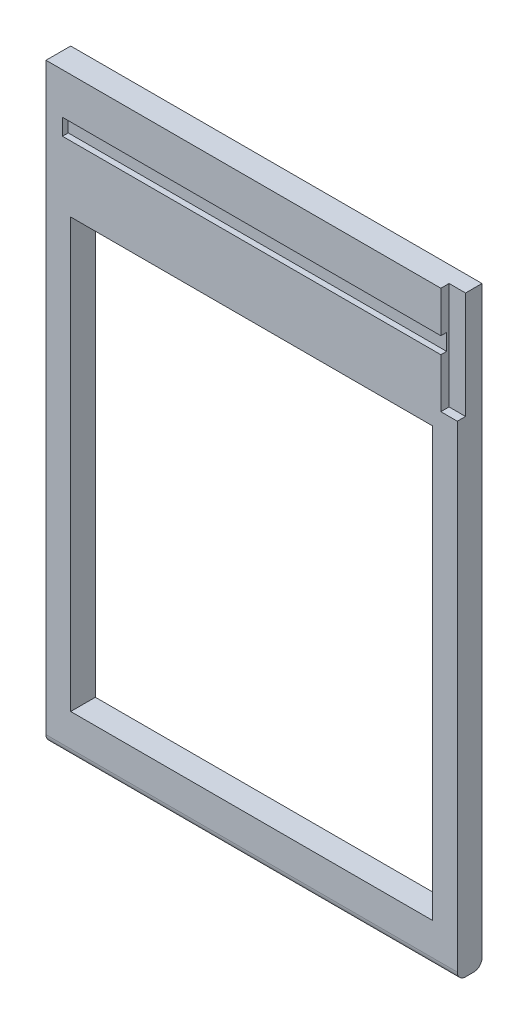
SolidWorks part; units mm, degrees
ref_plane "Alzado" through (0, 0, 0) normal (0, 0, 1) x (1, 0, 0)
ref_plane "Planta" through (0, 0, 0) normal (0, 1, 0) x (1, 0, 0)
ref_plane "Vista lateral" through (0, 0, 0) normal (1, 0, 0) x (0, 0, -1)
sketch "Croquis2" plane through (0, 0, 0) normal (0, 0, 1) x (1, 0, 0)
  line L1 (250, -360) -> (-250, -360)
  line L2 (250, -360) -> (250, 360)
  line L3 (250, 360) -> (-250, 360)
  line L4 (-250, -360) -> (-250, 360)
  line L5 (250, -360) -> (-250, 360) construction
  line L6 (250, 360) -> (-250, -360) construction
  point P0 (0, 0)
  dimension "D1" = 720
  dimension "D2" = 500
extrude "Saliente-Extruir1" add sketch "Croquis2" along normal blind 30
sketch "Croquis3" plane through (0, 0, 0) normal (0, 0, -1) x (-1, 0, 0)
  line L0 (-250, 360) -> (250, 360) construction
  line L1 (220, -310.6162) -> (-220, -310.6162)
  line L2 (220, -310.6162) -> (220, 210)
  line L3 (220, 210) -> (-220, 210)
  line L4 (-220, -310.6162) -> (-220, 210)
  line L5 (220, -310.6162) -> (-220, 210) construction
  line L6 (220, 210) -> (-220, -310.6162) construction
  line L7 (-250, -360) -> (-250, 360) construction
  line L9 (250, 360) -> (250, -360) construction
  point P0 (0, -50.3081)
  dimension "D1" = 150
  dimension "D2" = 440
  dimension "D3" = 30
  dimension "D4" = 30
extrude "Cortar-Extruir1" cut sketch "Croquis3" against normal through all
fillet "Redondeo1" radius 10 1 edges at (0, -360, 0)
fillet "Redondeo2" radius 10 1 edges at (0, -360, 30)
sketch "Croquis4" plane through (0, 0, 0) normal (0, 0, -1) x (-1, 0, 0)
  line L1 (-220, 329.0281) -> (220, 329.0281)
  line L2 (-220, 329.0281) -> (-220, 239.0281)
  line L3 (-220, 239.0281) -> (220, 239.0281)
  line L4 (220, 329.0281) -> (220, 239.0281)
  line L5 (-220, 329.0281) -> (220, 239.0281) construction
  line L6 (-220, 239.0281) -> (220, 329.0281) construction
  line L7 (250, 360) -> (250, -350) construction
  point P0 (0, 284.0281)
  dimension "D1" = 440
  dimension "D2" = 90
  dimension "D3" = 30
extrude "Cortar-Extruir4" cut sketch "Croquis4" against normal blind 5
sketch "Croquis9" plane through (0, 0, 30) normal (0, 0, 1) x (1, 0, 0)
  line L0 (-250, 360) -> (-250, -350) construction
  line L1 (250, 310) -> (-230, 310)
  line L2 (250, 310) -> (250, 290)
  line L3 (250, 290) -> (-230, 290)
  line L4 (-230, 310) -> (-230, 290)
  line L5 (250, 310) -> (-230, 290) construction
  line L6 (250, 290) -> (-230, 310) construction
  line L7 (250, 360) -> (-250, 360) construction
  point P0 (10, 300)
  dimension "D1" = 20
  dimension "D2" = 480
  dimension "D3" = 50
  dimension "D4" = 20
extrude "Cortar-Extruir6" cut sketch "Croquis9" against normal blind 7
sketch "Croquis10" plane through (250, 0, 0) normal (1, 0, 0) x (0, 0, -1)
  line L0 (-30, 310) -> (-30, 360) construction
  line L1 (-20, 230) -> (-30, 230)
  line L2 (-20, 230) -> (-20, 360)
  line L3 (-20, 360) -> (-30, 360)
  line L4 (-30, 230) -> (-30, 360)
  line L5 (-20, 230) -> (-30, 360) construction
  line L6 (-20, 360) -> (-30, 230) construction
  line L7 (-30, 360) -> (0, 360) construction
  point P0 (-25, 295)
  dimension "D1" = 130
  dimension "D2" = 0
  dimension "D3" = 10
extrude "Cortar-Extruir7" cut sketch "Croquis10" against normal blind 20
